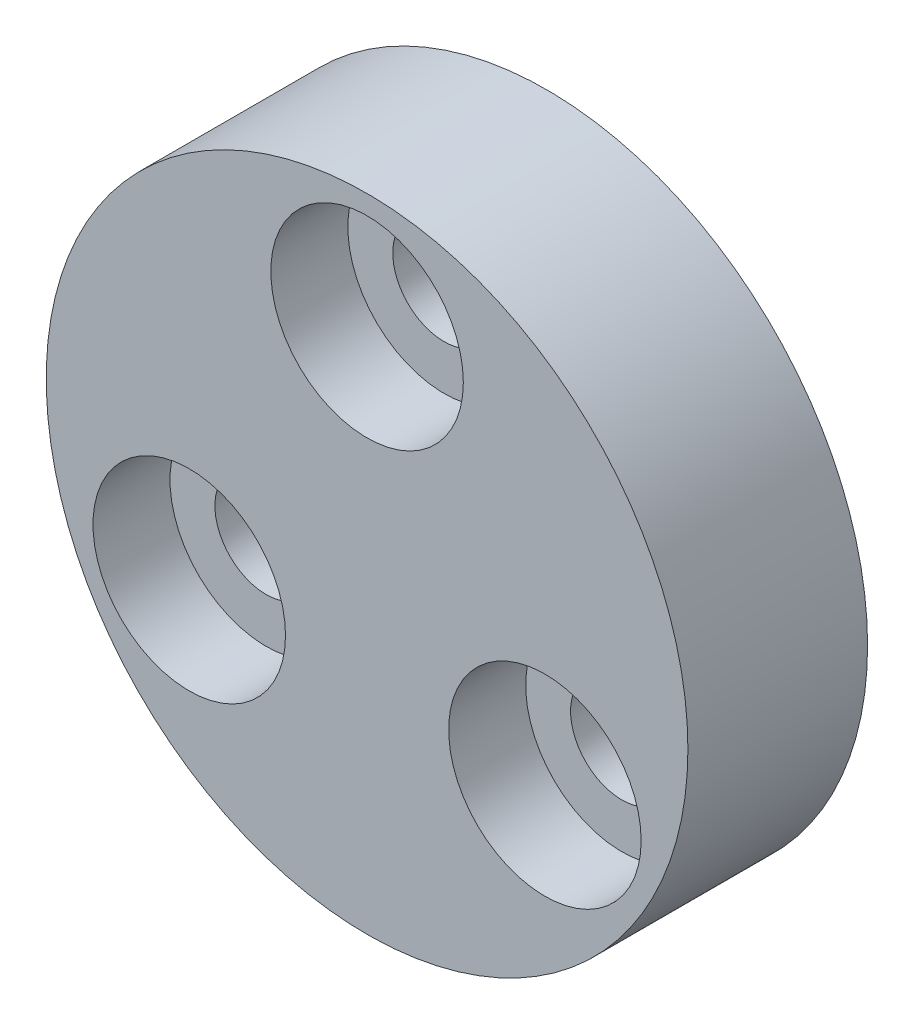
SolidWorks part; units mm, degrees
ref_plane "前视基准面" through (0, 0, 0) normal (0, 0, 1) x (1, 0, 0)
ref_plane "上视基准面" through (0, 0, 0) normal (0, 1, 0) x (1, 0, 0)
ref_plane "右视基准面" through (0, 0, 0) normal (1, 0, 0) x (0, 0, -1)
sketch "草图1" plane through (0, 0, 0) normal (0, 0, 1) x (1, 0, 0)
  circle A0 centre (0, 0) radius 12.5
  circle A1 centre (0, 0) radius 8 construction
  circle A2 centre (0, 8) radius 2
  circle A3 centre (6.9282, -4) radius 2
  circle A4 centre (-6.9282, -4) radius 2
  dimension "D1" = 25
  dimension "D2" = 16
  dimension "D3" = 4
  dimension "D4" = 3
extrude "凸台-拉伸1" add sketch "草图1" along normal blind 4
sketch "草图2" plane through (0, 0, 4) normal (0, 0, 1) x (1, 0, 0)
  circle A0 centre (0, 0) radius 12.5
  circle A1 centre (0, 8) radius 3.75
  circle A2 centre (6.9282, -4) radius 3.75
  circle A3 centre (-6.9282, -4) radius 3.75
  dimension "D1" = 7.5
  dimension "D2" = 3
extrude "凸台-拉伸2" add sketch "草图2" along normal blind 3
